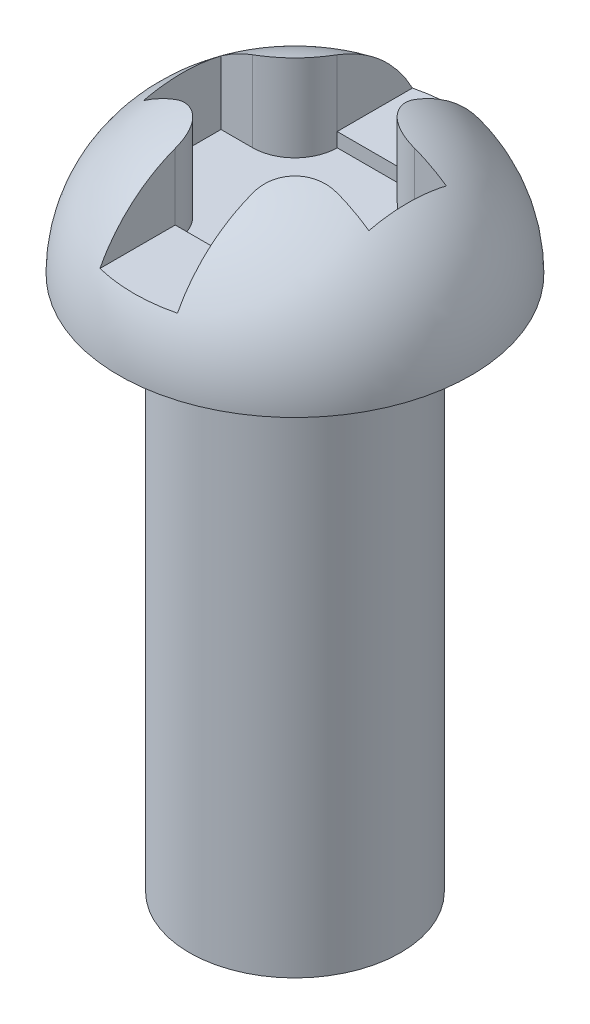
SolidWorks part; units mm, degrees
ref_plane "Front Plane" through (0, 0, 0) normal (0, 0, 1) x (1, 0, 0)
ref_plane "Top Plane" through (0, 0, 0) normal (0, 1, 0) x (1, 0, 0)
ref_plane "Right Plane" through (0, 0, 0) normal (1, 0, 0) x (0, 0, -1)
sketch "Sketch1" plane through (0, 0, 0) normal (1, 0, 0) x (0, 0, -1)
  line L1 (0, 0) -> (2.5, 0)
  line L2 (0, 0) -> (0, 2)
  line L3 (0, 2) -> (2.5, 2)
  line L4 (2.5, 0) -> (2.5, 2)
  arc A0 (2.5, 0) -> (0.5, 2) centre (0.5, 0) ccw
  dimension "D1" = 2.5
  dimension "D2" = 2
revolve "Revolve1" add sketch "Sketch1" angle 360 about L2
sketch "Sketch3" plane through (0, 2, 0) normal (0, 1, 0) x (1, 0, 0)
  line L1 (0.55, -2.45) -> (-0.55, -2.45)
  line L2 (0.55, -2.45) -> (0.55, 2.45)
  line L3 (0.55, 2.45) -> (-0.55, 2.45)
  line L4 (-0.55, -2.45) -> (-0.55, 2.45)
  line L5 (0.55, -2.45) -> (-0.55, 2.45) construction
  line L6 (0.55, 2.45) -> (-0.55, -2.45) construction
  point P0 (0, 0)
  dimension "D1" = 1.1
  dimension "D2" = 4.9
extrude "Cut-Extrude1" cut sketch "Sketch3" against normal offset from surface (1.1 mm away) 0.9 up to face at (0, 0, -2.5)
sketch "Sketch4" plane through (0, 0.9, 0) normal (0, 1, 0) x (1, 0, 0)
  line L0 (-0.55, 2.2189) -> (0.55, 2.2189) construction
  line L1 (-1.6, -0.55) -> (1.6, -0.55)
  line L2 (-1.6, -0.55) -> (-1.6, 0.55)
  line L3 (-1.6, 0.55) -> (1.6, 0.55)
  line L4 (1.6, -0.55) -> (1.6, 0.55)
  line L5 (-1.6, -0.55) -> (1.6, 0.55) construction
  line L6 (-1.6, 0.55) -> (1.6, -0.55) construction
  point P0 (0, 0)
  dimension "D1" = 3.2
extrude "Cut-Extrude2" cut sketch "Sketch4" along normal through all
fillet "Fillet1" radius 0.6 4 edges at (0.55, 1.4403, 0.55) (-0.55, 1.4403, 0.55) (0.55, 1.4403, -0.55) (-0.55, 1.4403, -0.55)
sketch "Sketch5" plane through (0, 0.9, 0) normal (0, 1, 0) x (1, 0, 0)
  line L0 (-0.55, 1.15) -> (0.55, 1.15)
  line L1 (0.55, -1.15) -> (-0.55, -1.15)
  line L2 (-1.15, 0.55) -> (-1.6, 0.55)
  line L3 (-1.6, 0.55) -> (-1.6, -0.55)
  line L4 (-1.6, -0.55) -> (-1.15, -0.55)
  line L5 (1.15, -0.55) -> (1.6, -0.55)
  line L6 (1.6, -0.55) -> (1.6, 0.55)
  line L7 (1.6, 0.55) -> (1.15, 0.55)
  arc A0 (1.15, 0.55) -> (0.55, 1.15) centre (1.15, 1.15) cw
  arc A1 (1.15, -0.55) -> (0.55, -1.15) centre (1.15, -1.15) ccw
  arc A2 (-0.55, -1.15) -> (-1.15, -0.55) centre (-1.15, -1.15) ccw
  arc A3 (-1.15, 0.55) -> (-0.55, 1.15) centre (-1.15, 1.15) ccw
  arc A4 (0.55, 1.15) -> (1.15, 0.55) centre (1.15, 1.15) ccw construction
  arc A5 (1.15, -0.55) -> (0.55, -1.15) centre (1.15, -1.15) ccw construction
  arc A6 (-1.15, 0.55) -> (-0.55, 1.15) centre (-1.15, 1.15) ccw construction
  arc A7 (-0.55, -1.15) -> (-1.15, -0.55) centre (-1.15, -1.15) ccw construction
extrude "Cut-Extrude3" cut sketch "Sketch5" against normal blind 0.2
sketch "Sketch2" plane through (0, 0, 0) normal (0, -1, 0) x (1, 0, 0)
  circle A0 centre (0, 0) radius 1.5
  dimension "D1" = 3
extrude "Boss-Extrude1" add sketch "Sketch2" along normal blind 7.6
